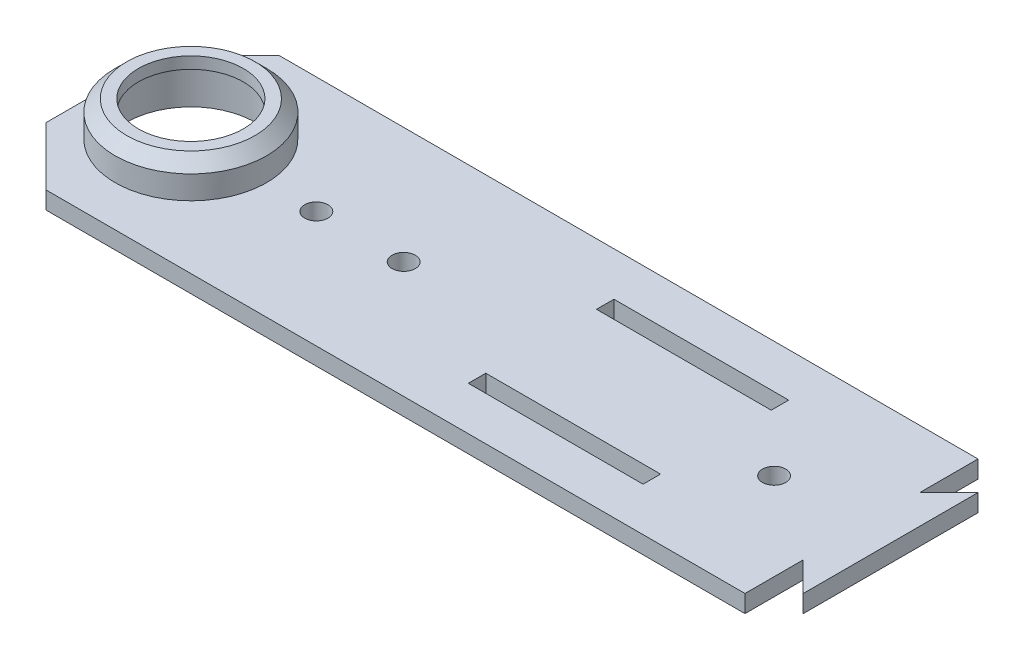
SolidWorks part; units mm, degrees
ref_plane "Alzado" through (0, 0, 0) normal (0, 0, 1) x (1, 0, 0)
ref_plane "Planta" through (0, 0, 0) normal (0, 1, 0) x (1, 0, 0)
ref_plane "Vista lateral" through (0, 0, 0) normal (1, 0, 0) x (0, 0, -1)
sketch "Croquis1" plane through (0, 0, 0) normal (0, 1, 0) x (1, 0, 0)
  line L0 (65, 10) -> (70, 15)
  line L1 (-65, -20) -> (65, -20)
  line L2 (-65, -20) -> (-65, 20)
  line L3 (-65, 20) -> (65, 20)
  line L4 (65, -20) -> (65, -10)
  line L5 (-65, -20) -> (65, 20) construction
  line L6 (-65, 20) -> (65, -20) construction
  line L7 (70, 15) -> (70, -15)
  line L8 (70, -15) -> (65, -10)
  line L9 (65, 10) -> (65, 20)
  line L10 (0, 0) -> (77.1384, 0) construction
  line L12 (10, 9.5) -> (40, 9.5)
  line L13 (10, 9.5) -> (10, 12.5)
  line L14 (10, 12.5) -> (40, 12.5)
  line L15 (40, 9.5) -> (40, 12.5)
  line L16 (10, 9.5) -> (40, 12.5) construction
  line L17 (10, 12.5) -> (40, 9.5) construction
  line L18 (10, -12.5) -> (40, -12.5)
  line L19 (10, -12.5) -> (10, -9.5)
  line L20 (10, -9.5) -> (40, -9.5)
  line L21 (40, -12.5) -> (40, -9.5)
  line L22 (10, -12.5) -> (40, -9.5) construction
  line L23 (10, -9.5) -> (40, -12.5) construction
  circle A2 centre (-50.1299, 0) radius 11
  circle A3 centre (-50.1299, 0) radius 12.5 construction
  circle A4 centre (-28.5951, 0) radius 2
  circle A5 centre (-13.5951, 0) radius 2
  circle A6 centre (50, 0) radius 2
  point P0 (0, 0)
  point P8 (70, 0)
  point P11 (-65.0987, -19.9687)
  point P13 (-64.6762, -19.9004)
  point P14 (-64.6723, 19.8992)
  point P16 (-64.9006, 19.9694)
  point P19 (25, 11)
  point P35 (25, -11)
  dimension "D8" = 22
  dimension "D12" = 25
  dimension "D13" = 4
  dimension "D14" = 4
  dimension "D17" = 4
  dimension "D1" = 130
  dimension "D2" = 45
  dimension "D3" = 45
  dimension "D4" = 20
  dimension "D5" = 30
  dimension "D6" = 40
  dimension "D9" = 3
  dimension "D10" = 30
  dimension "D11" = 40
  dimension "D15" = 15
  dimension "D16" = 10
  dimension "D18" = 12.5
  dimension "D19" = 12.5
extrude "Saliente-Extruir1" add sketch "Croquis1" along normal blind 3
sketch "Croquis2" plane through (0, 3, 0) normal (0, 1, 0) x (1, 0, 0)
  circle A0 centre (-50.1299, 0) radius 11
  circle A1 centre (-50.1299, 0) radius 13
  dimension "D1" = 2
extrude "Saliente-Extruir2" add sketch "Croquis2" along normal blind 4
sketch "Croquis3" plane through (0, 7, 0) normal (0, 1, 0) x (1, 0, 0)
  circle A0 centre (-50.1299, 0) radius 13
  circle A1 centre (-50.1299, 0) radius 9
  dimension "D1" = 18
extrude "Saliente-Extruir3" add sketch "Croquis3" along normal blind 2
chamfer "Chaflán1" distance 2 angle 45 1 edges at (-50.1299, 9, 13)
chamfer "Chaflán2" distance 10 angle 45 2 edges at (-65, 1.5, 20) (-65, 1.5, -20)
